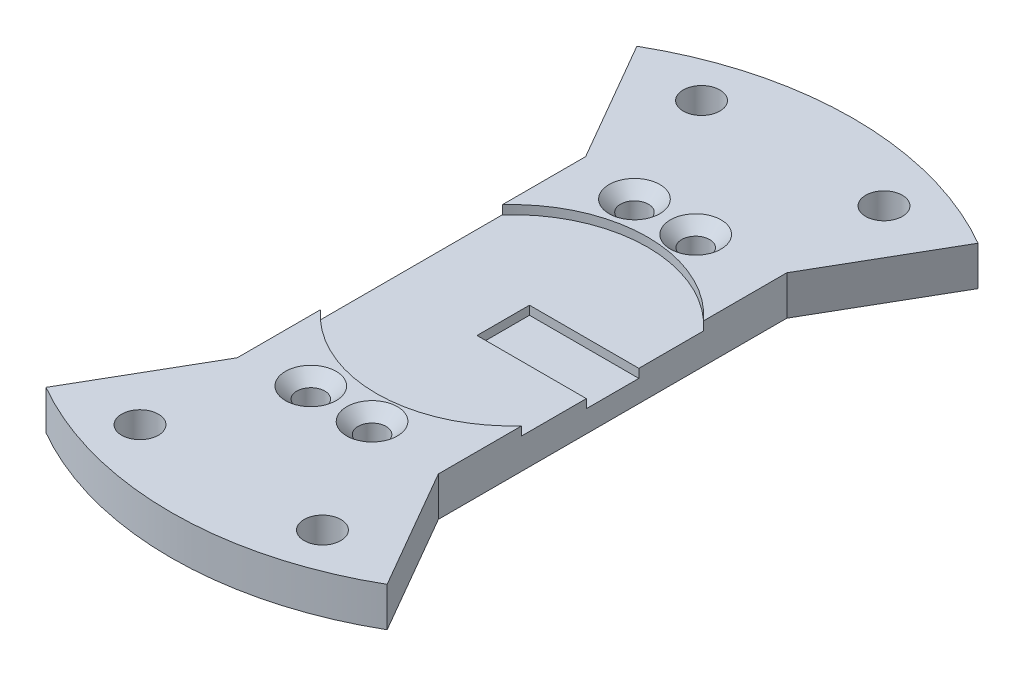
SolidWorks part; units mm, degrees
ref_plane "Front Plane" through (0, 0, 0) normal (0, 0, 1) x (1, 0, 0)
ref_plane "Top Plane" through (0, 0, 0) normal (0, 1, 0) x (1, 0, 0)
ref_plane "Right Plane" through (0, 0, 0) normal (1, 0, 0) x (0, 0, -1)
sketch "Sketch1" plane through (0, 0, 0) normal (0, 1, 0) x (1, 0, 0)
  line L0 (-33.75, 0) -> (0, 0) construction
  line L1 (0, 0) -> (-19.5, 33.775)
  line L2 (0, 0) -> (19.5, 33.775)
  line L3 (0, 0) -> (0, 39) construction
  line L4 (0, 0) -> (-19.5, -33.775)
  line L5 (0, 0) -> (19.5, -33.775)
  line L6 (-11.5, 19.9186) -> (-11.5, -19.9186)
  line L7 (11.5, 19.9186) -> (11.5, -19.9186)
  circle A0 centre (0, 0) radius 39
  circle A1 centre (-33.75, 0) radius 2.1
  circle A2 centre (-27.3043, 19.8378) radius 2.1
  circle A3 centre (-10.4293, 32.0982) radius 2.1
  circle A4 centre (10.4293, 32.0982) radius 2.1
  circle A5 centre (27.3043, 19.8378) radius 2.1
  circle A6 centre (33.75, 0) radius 2.1
  circle A7 centre (27.3043, -19.8378) radius 2.1
  circle A8 centre (10.4293, -32.0982) radius 2.1
  circle A9 centre (-10.4293, -32.0982) radius 2.1
  circle A10 centre (-27.3043, -19.8378) radius 2.1
  dimension "D1" = 78
  dimension "D3" = 4.2
  dimension "D2" = 33.75
  dimension "D5" = 30
  dimension "D6" = 30
  dimension "D7" = 30
  dimension "D8" = 30
  dimension "D9" = 23
  dimension "D10" = 11.5
  dimension "D4" = 10
extrude "Boss-Extrude1" add sketch "Sketch1" along normal blind 4.5 contours L4 A0 L5 A9 A8 | L7 L2 L5 | L2 A0 L1 A4 A3 | L1 L6 L4
sketch "Sketch2" plane through (0, 4.5, 0) normal (0, 1, 0) x (1, 0, 0)
  circle A0 centre (0, 0) radius 15.5
  dimension "D1" = 31
extrude "Cut-Extrude1" cut sketch "Sketch2" against normal blind 1
sketch "Sketch3" plane through (0, 3.5, 0) normal (0, 1, 0) x (1, 0, 0)
  line L0 (11.5, 10.3923) -> (11.5, -10.3923) construction
  line L1 (11.5, 3) -> (-1, 3)
  line L2 (11.5, 3) -> (11.5, -3)
  line L3 (11.5, -3) -> (-1, -3)
  line L4 (-1, 3) -> (-1, -3)
  dimension "D1" = 12.5
  dimension "D2" = 6
  dimension "D3" = 3
extrude "Cut-Extrude2" cut sketch "Sketch3" against normal blind 1
sketch "Sketch4" plane through (0, 4.5, 0) normal (0, 1, 0) x (1, 0, 0)
  line L0 (-11.5, 19.9186) -> (-11.5, 10.3923) construction
  circle A0 centre (-4.5, -18.5) radius 1.6
  circle A1 centre (2.5, -18.5) radius 1.6
  circle A2 centre (-4.5, 18.5) radius 1.6
  circle A3 centre (2.5, 18.5) radius 1.6
  point P8 (0, 0)
  point P9 (0, 0)
  point P10 (0, 0)
  point P11 (0, 0)
  dimension "D1" = 3.2
  dimension "D2" = 3.2
  dimension "D3" = 3.2
  dimension "D4" = 3.2
  dimension "D5" = 7
  dimension "D6" = 7
  dimension "D7" = 37
  dimension "D8" = 18.5
extrude "Cut-Extrude3" cut sketch "Sketch4" against normal through all
hole_wizard "CSK for M4 Countersunk Flat Head Screw1" positions "3DSketch1" profile "Sketch5" countersink size "M4" standard "ISO" end condition through all
sketch3d "3DSketch1"
  line L0 (-4.5, 0, 18.5) -> (-4.5, 4.5, 18.5) construction
  line L1 (2.5, 0, 18.5) -> (2.5, 4.5, 18.5) construction
  line L2 (-4.5, 0, -18.5) -> (-4.5, 4.5, -18.5) construction
  line L3 (2.5, 0, -18.5) -> (2.5, 4.5, -18.5) construction
  point P0 (-4.5, 4.5, 18.5)
  point P4 (2.5, 4.5, 18.5)
  point P8 (-4.5, 4.5, -18.5)
  point P12 (2.5, 4.5, -18.5)
sketch "Sketch5" plane through (-4.5, 4.5, 18.5) normal (1, 0, 0) x (0, 0, 1)
  line L0 (0, 0) -> (0, 4.5)
  line L1 (0, 4.5) -> (1.6, 4.5)
  line L2 (1.6, 4.5) -> (1.6, 1.3)
  line L3 (1.6, 1.3) -> (2.9, 0)
  line L5 (2.9, 0) -> (0, 0)
  line L6 (-1.6, 1.3) -> (-2.9, 0) construction
  line L11 (0, -6.35) -> (0, 107.95) construction
  dimension "Thru Hole Dia." = 3.2
  dimension "Thru Hole Depth" = 4.5
  dimension "Near C'Sink Dia." = 5.8
  dimension "Near C'Sink Angle" = 90
